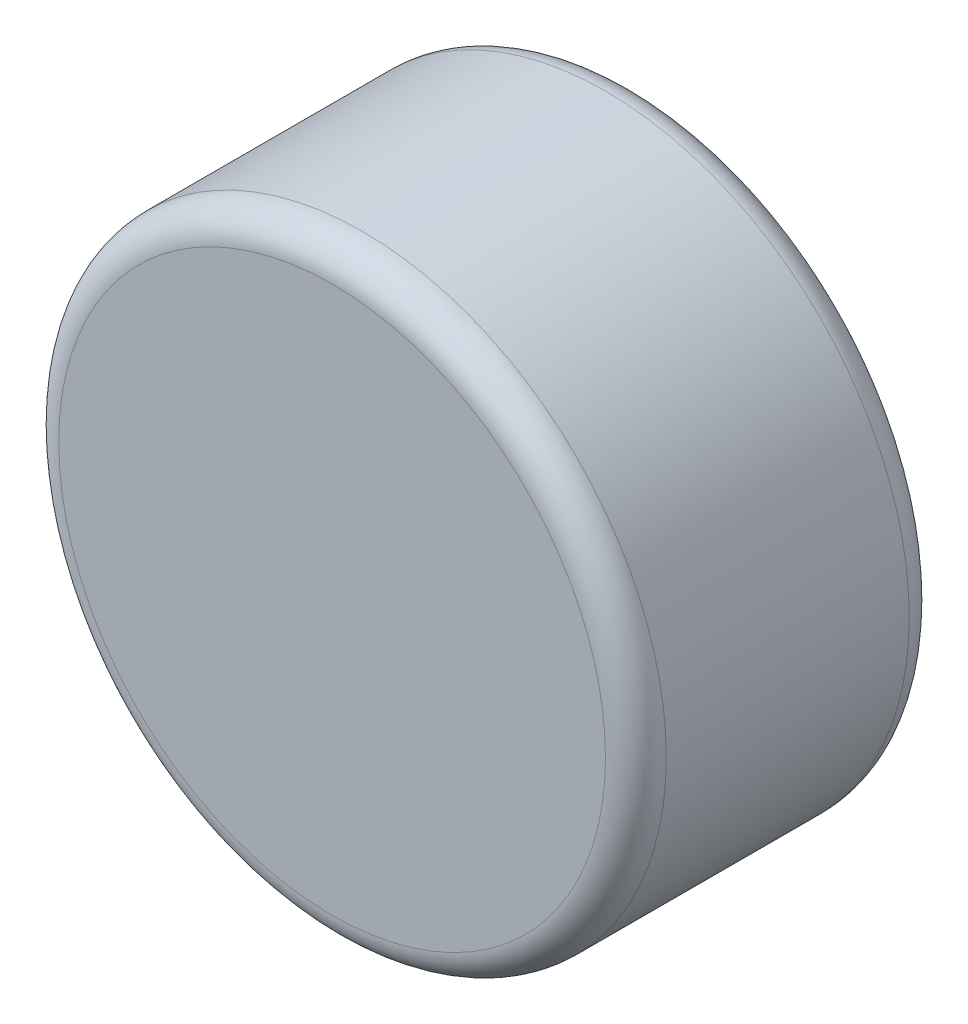
SolidWorks part; units mm, degrees
ref_plane "Front Plane" through (0, 0, 0) normal (0, 0, 1) x (1, 0, 0)
ref_plane "Top Plane" through (0, 0, 0) normal (0, 1, 0) x (1, 0, 0)
ref_plane "Right Plane" through (0, 0, 0) normal (1, 0, 0) x (0, 0, -1)
sketch "Sketch1" plane through (0, 0, 0) normal (0, 0, 1) x (1, 0, 0)
  circle A0 centre (0, 0) radius 2
  dimension "D1" = 4
extrude "Boss-Extrude1" add sketch "Sketch1" along normal blind 2
fillet "Fillet1" radius 0.2 2 edges at (2, 0, 0) (2, 0, 2)
